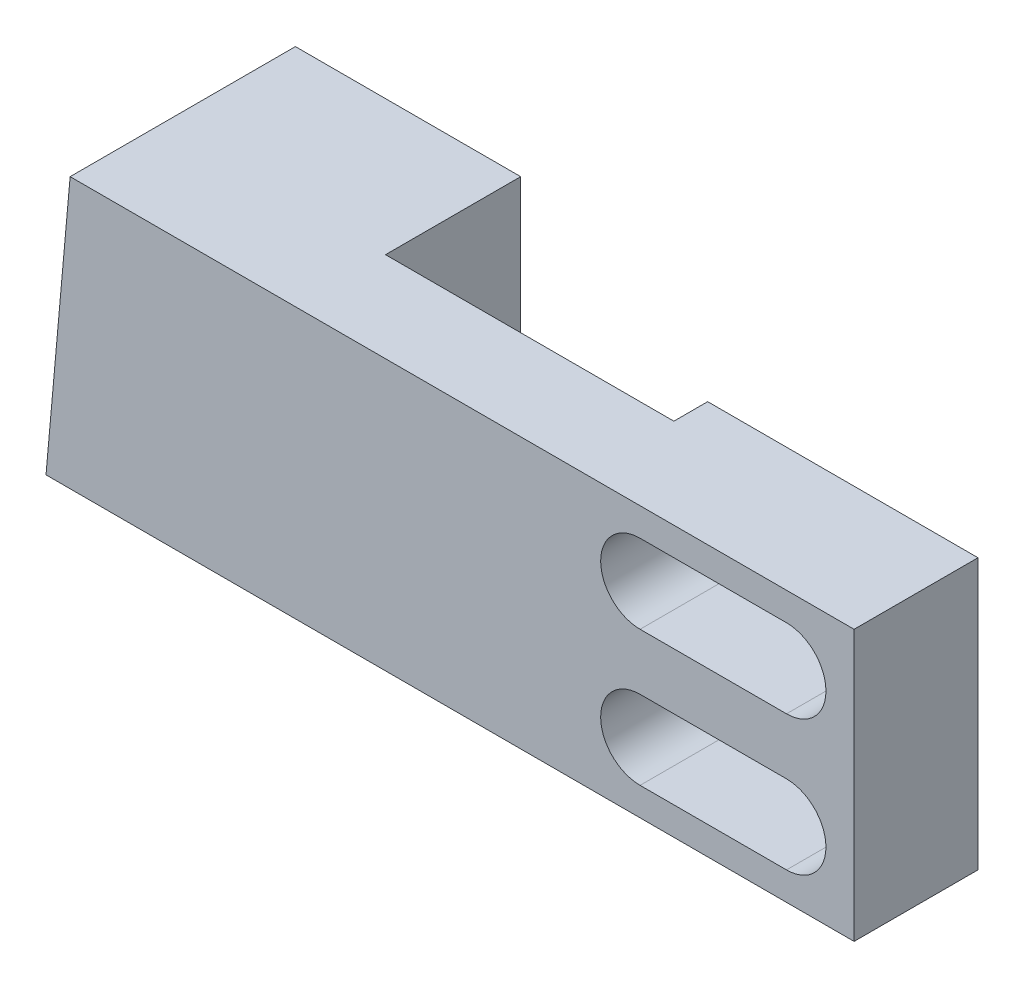
SolidWorks part; units mm, degrees
ref_plane "前视基准面" through (0, 0, 0) normal (0, 0, 1) x (1, 0, 0)
ref_plane "上视基准面" through (0, 0, 0) normal (0, 1, 0) x (1, 0, 0)
ref_plane "右视基准面" through (0, 0, 0) normal (1, 0, 0) x (0, 0, -1)
sketch "草图1" plane through (0, 0, 0) normal (0, 0, 1) x (1, 0, 0)
  line L0 (0, 0) -> (0, 12)
  line L1 (0, 12) -> (-10, 12)
  line L2 (-10, 12) -> (-11.071, 0)
  line L3 (-11.071, 0) -> (0, 0)
  dimension "D1" = 84.9
  dimension "D2" = 10
  dimension "D3" = 12
extrude "凸台-拉伸1" add sketch "草图1" along normal blind 10
sketch "草图2" plane through (0, 0, 10) normal (0, 0, 1) x (1, 0, 0)
  line L0 (-1003.2655, 12) -> (48996.7345, 12) construction
  line L2 (-1003.0506, 0) -> (48996.9494, 0) construction
  line L5 (0, 12) -> (24.8, 12)
  line L6 (0, 12) -> (0, 0)
  line L7 (0, 0) -> (24.8, 0)
  line L8 (24.8, 12) -> (24.8, 0)
  dimension "D1" = 24.8
extrude "凸台-拉伸2" add sketch "草图2" against normal blind 4
sketch "草图3" plane through (0, 0, 6) normal (0, 0, -1) x (-1, 0, 0)
  line L0 (0, 0) -> (-24.8, 0) construction
  line L1 (-24.8, 12) -> (-12.8, 12)
  line L2 (-24.8, 12) -> (-24.8, 0)
  line L3 (-24.8, 0) -> (-12.8, 0)
  line L4 (-12.8, 12) -> (-12.8, 0)
  dimension "D1" = 12
extrude "凸台-拉伸3" add sketch "草图3" along normal blind 1.5
sketch "草图5" plane through (0, 0, 10) normal (0, 0, 1) x (1, 0, 0)
  line L0 (-975.2, 6) -> (49024.8, 6) construction
  line L1 (24.8, 0) -> (24.8, 12) construction
  line L2 (-973.6088, 9) -> (49026.3912, 9) construction
  line L3 (21.8, 9) -> (15.3, 9) construction
  line L4 (21.8, 7.25) -> (15.3, 7.25)
  line L5 (21.8, 10.75) -> (15.3, 10.75)
  line L6 (21.8, 3) -> (15.3, 3) construction
  line L7 (21.8, 4.75) -> (15.3, 4.75)
  line L8 (21.8, 1.25) -> (15.3, 1.25)
  arc A0 (21.8, 7.25) -> (21.8, 10.75) centre (21.8, 9) ccw
  arc A1 (15.3, 10.75) -> (15.3, 7.25) centre (15.3, 9) ccw
  arc A2 (21.8, 4.75) -> (21.8, 1.25) centre (21.8, 3) cw
  arc A3 (15.3, 1.25) -> (15.3, 4.75) centre (15.3, 3) cw
  point P5 (24.8, 6)
  point P9 (18.55, 9)
  point P16 (18.55, 3)
  dimension "D2" = 1.75
  dimension "D1" = 3
  dimension "D3" = 6.5
  dimension "D4" = 3
extrude "切除-拉伸1" cut sketch "草图5" against normal through all
